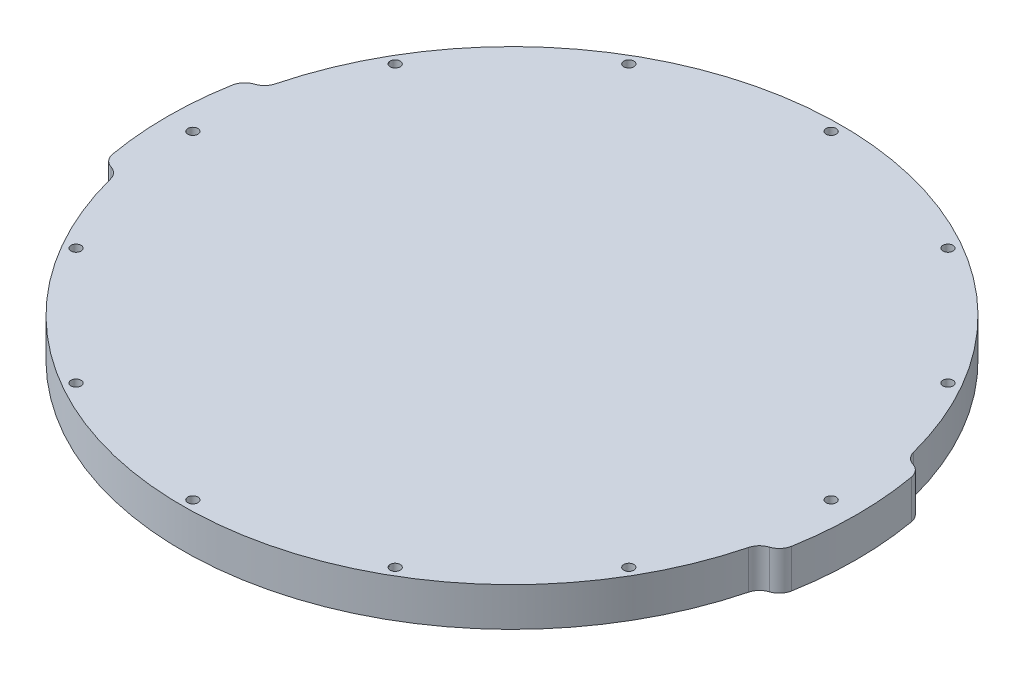
SolidWorks part; units mm, degrees
material "Acrylic (Medium-high impact)"
ref_plane "Front Plane" through (0, 0, 0) normal (0, 0, 1) x (1, 0, 0)
ref_plane "Top Plane" through (0, 0, 0) normal (0, 1, 0) x (1, 0, 0)
ref_plane "Right Plane" through (0, 0, 0) normal (1, 0, 0) x (0, 0, -1)
sketch "Sketch1" plane through (0, 0, 0) normal (0, 1, 0) x (1, 0, 0)
  line L0 (0, 0) -> (-111.234, 19.6136) construction
  line L1 (0, 0) -> (-139.7786, 0) construction
  line L2 (0, 0) -> (-111.234, -19.6136) construction
  line L3 (0, 0) -> (111.234, 19.6136) construction
  line L4 (0, 0) -> (111.234, -19.6136) construction
  circle A0 centre (0, 0) radius 104.55 construction
  circle A1 centre (0, 104.55) radius 1.65
  circle A2 centre (52.275, 90.543) radius 1.65
  circle A3 centre (90.543, 52.275) radius 1.65
  circle A4 centre (104.55, 0) radius 1.65
  circle A5 centre (90.543, -52.275) radius 1.65
  circle A6 centre (52.275, -90.543) radius 1.65
  circle A7 centre (0, -104.55) radius 1.65
  circle A8 centre (-52.275, -90.543) radius 1.65
  circle A9 centre (-90.543, -52.275) radius 1.65
  circle A10 centre (-104.55, 0) radius 1.65
  circle A11 centre (-90.543, 52.275) radius 1.65
  circle A12 centre (-52.275, 90.543) radius 1.65
  circle A13 centre (0, 0) radius 107.95 construction
  circle A14 centre (0, 0) radius 112.95 construction
  arc A15 (-111.234, -19.6136) -> (-111.234, 19.6136) centre (0, 0) cw
  arc A16 (111.234, -19.6136) -> (111.234, 19.6136) centre (0, 0) ccw
  arc A17 (-111.234, -19.6136) -> (-105.328, -23.6479) centre (-106.31, -18.7453) ccw
  arc A18 (-111.234, 19.6136) -> (-105.328, 23.6479) centre (-106.31, 18.7453) cw
  arc A19 (111.234, -19.6136) -> (105.328, -23.6479) centre (106.31, -18.7453) cw
  arc A20 (111.234, 19.6136) -> (105.328, 23.6479) centre (106.31, 18.7453) ccw
  arc A21 (-105.328, 23.6479) -> (105.328, 23.6479) centre (0, 0) cw
  arc A22 (105.328, -23.6479) -> (-105.328, -23.6479) centre (0, 0) cw
  point P30 (0, 0)
  dimension "D1" = 3.3
  dimension "D2" = 209.1
  dimension "D4" = 215.9
  dimension "D5" = 5
  dimension "D6" = 10
  dimension "D3" = 12
extrude "Boss-Extrude1" add sketch "Sketch1" along normal blind 12.7
fillet "Fillet1" radius 5 4 edges at (105.328, 6.35, 23.6479) (105.328, 6.35, -23.6479) (-105.328, 6.35, -23.6479) (-105.328, 6.35, 23.6479)
